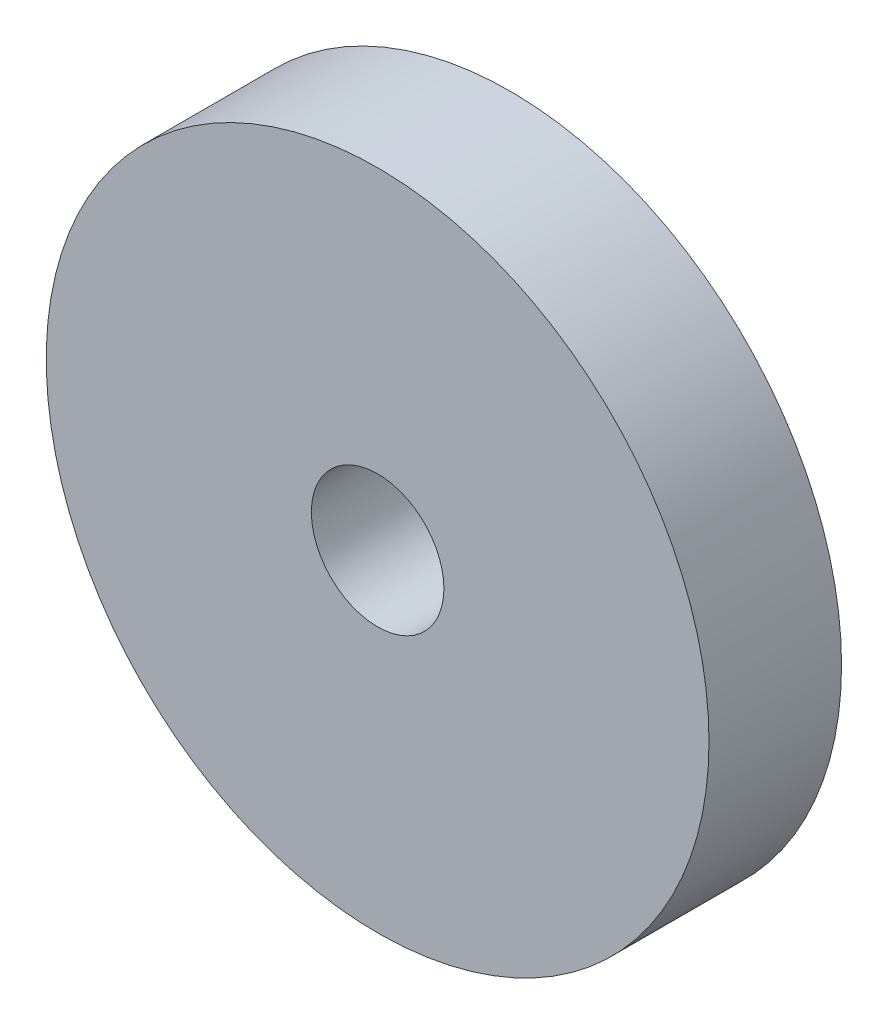
SolidWorks part; units mm, degrees
material "Rubber"
ref_plane "Front Plane" through (0, 0, 0) normal (0, 0, 1) x (1, 0, 0)
ref_plane "Top Plane" through (0, 0, 0) normal (0, 1, 0) x (1, 0, 0)
ref_plane "Right Plane" through (0, 0, 0) normal (1, 0, 0) x (0, 0, -1)
sketch "Sketch1" plane through (0, 0, 0) normal (0, 0, 1) x (1, 0, 0)
  circle A0 centre (0, 0) radius 50
  circle A1 centre (0, 0) radius 10
  dimension "D1" = 100
extrude "Boss-Extrude1" add sketch "Sketch1" along normal blind 20
